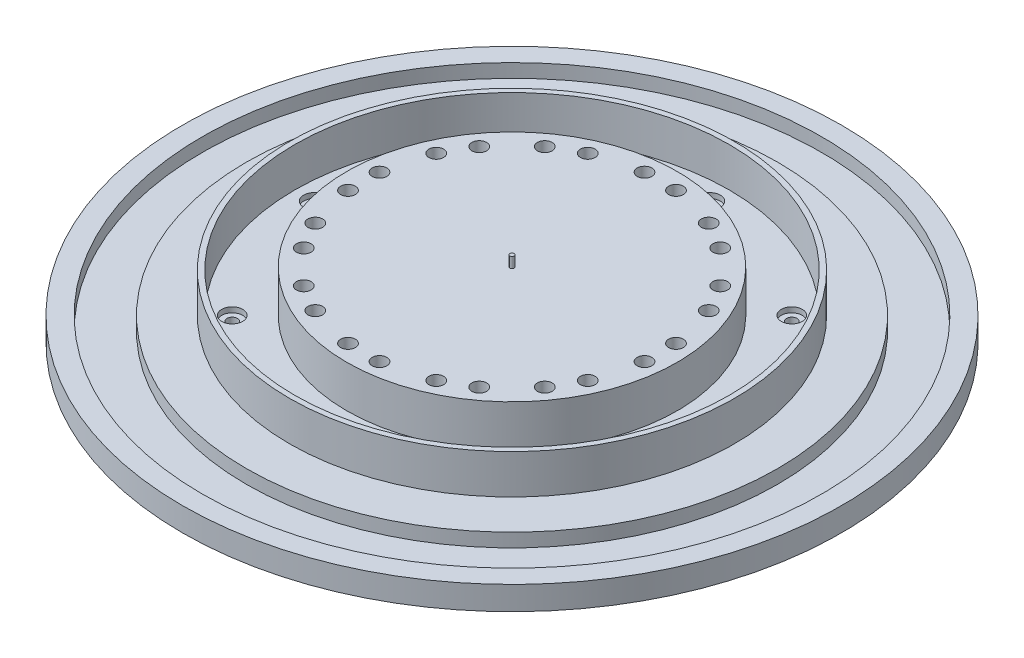
SolidWorks part; units mm, degrees
material "AISI 304"
ref_plane "Front Plane" through (0, 0, 0) normal (0, 0, 1) x (1, 0, 0)
ref_plane "Top Plane" through (0, 0, 0) normal (0, 1, 0) x (1, 0, 0)
ref_plane "Right Plane" through (0, 0, 0) normal (1, 0, 0) x (0, 0, -1)
sketch "Sketch3" plane through (0, 0, 0) normal (1, 0, 0) x (0, 0, -1)
  line L0 (-212, 8.0703) -> (-212, 45.5703)
  line L1 (-314, 8.0703) -> (-295, 8.0703)
  line L2 (-314, 8.0703) -> (-314, -14.4297)
  line L5 (-295, 8.0703) -> (-295, -4.9297)
  line L6 (-295, -4.9297) -> (-253, -4.9297)
  line L7 (-212, 45.5703) -> (-207, 45.5703)
  line L9 (-253, -4.9297) -> (-253, 8.0703)
  line L10 (-253, 8.0703) -> (-212, 8.0703)
  line L11 (-314, -14.4297) -> (0, -14.4297)
  line L12 (0, 120.738) -> (0, -95.9334) construction
  line L13 (-207, 45.5703) -> (-207, 8.0703)
  line L15 (-207, 8.0703) -> (-0.8488, 8.0703)
  line L16 (0, 8.0703) -> (0, -14.4297)
  line L17 (-0.8488, 8.0703) -> (-0.8488, 11.7809)
  line L18 (-0.8488, 11.7809) -> (0, 11.7809)
  line L19 (0, 11.7809) -> (0, 8.0703)
  dimension "D1" = 22.5
  dimension "D2" = 590
  dimension "D4" = 5
  dimension "D5" = 212
  dimension "D6" = 13
  dimension "D7" = 42
revolve "Revolve1" add sketch "Sketch3" angle 360 about L12
sketch "Sketch6" plane through (0, 8.0703, 0) normal (0, 1, 0) x (1, 0, 0)
  line L0 (-1000, 0) -> (49000, 0) construction
  line L1 (0, -1000) -> (0, 49000) construction
  line L2 (-707.1068, -707.1068) -> (34648.2323, 34648.2323) construction
  line L3 (-707.1068, 707.1068) -> (34648.2323, -34648.2323) construction
  circle A5 centre (-133.2896, 133.2896) radius 10
  circle A7 centre (133.2896, 133.2896) radius 10
  circle A8 centre (-133.2896, -133.2896) radius 10
  circle A9 centre (133.2896, -133.2896) radius 10
  circle A10 centre (0, 0) radius 188.5 construction
  circle A11 centre (0, 188.5) radius 10
  circle A12 centre (188.5, 0) radius 10
  circle A13 centre (0, -188.5) radius 10
  circle A14 centre (-188.5, 0) radius 10
  point P24 (-119.8546, 119.8546)
  point P27 (119.8546, 119.8546)
  dimension "D1" = 20
  dimension "D2" = 20
  dimension "D3" = 20
  dimension "D5" = 20
  dimension "D7" = 20
  dimension "D8" = 20
  dimension "D9" = 377
  dimension "D4" = 188.5
  dimension "D6" = 19
  dimension "D10" = 188.5
extrude "Cut-Extrude2" cut sketch "Sketch6" against normal blind 5
sketch "Sketch7" plane through (0, 3.0703, 0) normal (0, 1, 0) x (1, 0, 0)
  line L0 (-1000, 0) -> (49000, 0) construction
  line L1 (0, -1000) -> (0, 49000) construction
  line L2 (-707.1068, -707.1068) -> (34648.2323, 34648.2323) construction
  line L3 (-707.1068, 707.1068) -> (34648.2323, -34648.2323) construction
  circle A0 centre (0, 188.5) radius 5
  circle A1 centre (133.2896, 133.2896) radius 5
  circle A2 centre (-133.2896, 133.2896) radius 5
  circle A3 centre (188.5, 0) radius 5
  circle A4 centre (133.2896, -133.2896) radius 5
  circle A5 centre (0, -188.5) radius 5
  circle A6 centre (-188.5, 0) radius 5
  circle A7 centre (-133.2896, -133.2896) radius 5
  dimension "D1" = 10
  dimension "D2" = 188.5
  dimension "12" = 10
extrude "Cut-Extrude3" cut sketch "Sketch7" against normal through all
sketch "Sketch8" plane through (0, 8.0703, 0) normal (0, 1, 0) x (1, 0, 0)
  circle A0 centre (0, 0) radius 157.5
  dimension "D1" = 315
extrude "Boss-Extrude1" add sketch "Sketch8" along normal blind 40
sketch "Sketch9" plane through (0, 48.0703, 0) normal (0, 1, 0) x (1, 0, 0)
  line L0 (-1000, 0) -> (49000, 0) construction
  line L1 (0, -1000) -> (0, 49000) construction
  circle A1 centre (-15, 141.25) radius 7
  circle A2 centre (15, 141.25) radius 7
  circle A3 centre (0, 0) radius 157.5 construction
  dimension "D3" = 14
  dimension "D4" = 14
  dimension "D1" = 30
  dimension "D2" = 15
  dimension "D5" = 141.25
extrude "Cut-Extrude4" cut sketch "Sketch9" against normal blind 35
pattern_circular "CirPattern1" count 12 over 360 about axis through (0, 0, 0) along (0, 1, 0) of "Cut-Extrude4"
sketch "Sketch10" plane through (0, 48.0703, 0) normal (0, 1, 0) x (1, 0, 0)
  circle A0 centre (0, 0) radius 2.0004
extrude "Boss-Extrude2" add sketch "Sketch10" along normal blind 10
